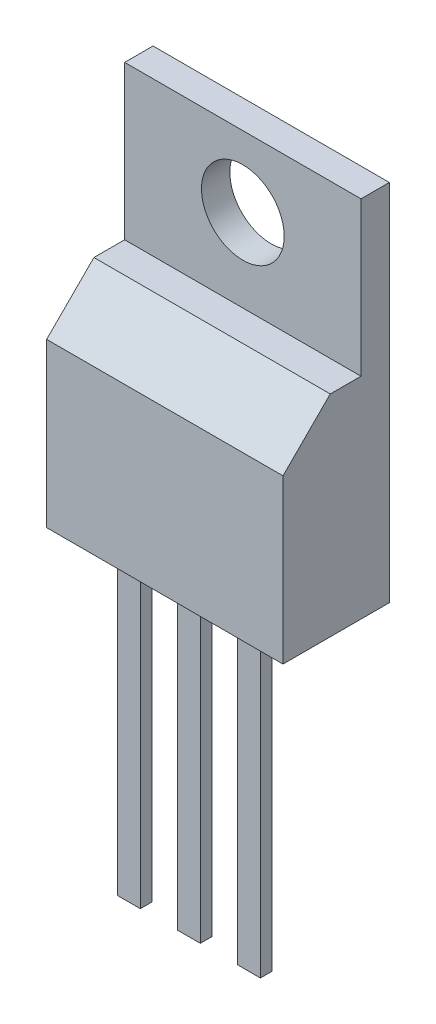
SolidWorks part; units mm, degrees
ref_plane "前视基准面" through (0, 0, 0) normal (0, 0, 1) x (1, 0, 0)
ref_plane "上视基准面" through (0, 0, 0) normal (0, 1, 0) x (1, 0, 0)
ref_plane "右视基准面" through (0, 0, 0) normal (1, 0, 0) x (0, 0, -1)
sketch "草图1" plane through (0, 0, 0) normal (0, 0, 1) x (1, 0, 0)
  line L0 (0, 13.5549) -> (0, -16.5771) construction
  line L1 (-5, 15.4) -> (5, 15.4)
  line L2 (-5, 15.4) -> (-5, 0)
  line L3 (-5, 0) -> (5, 0)
  line L4 (5, 15.4) -> (5, 0)
  line L5 (-12.7598, 0) -> (15.1062, 0) construction
  dimension "D1" = 15.4
  dimension "D2" = 10
extrude "凸台-拉伸1" add sketch "草图1" along normal blind 4.5
sketch "草图2" plane through (0, 0, 4.5) normal (0, 0, 1) x (1, 0, 0)
  line L0 (5, 0) -> (5, 15.4) construction
  line L1 (-5, 15.4) -> (5, 15.4)
  line L2 (-5, 15.4) -> (-5, 8.9)
  line L3 (-5, 8.9) -> (5, 8.9)
  line L4 (5, 15.4) -> (5, 8.9)
  dimension "D1" = 6.5
extrude "切除-拉伸1" cut sketch "草图2" against normal offset from surface (3.3 mm away) 1.2 up to face at (0, 7.7, 0)
chamfer "倒角1" distance 2 angle 45 1 edges at (0, 8.9, 4.5)
sketch "草图3" plane through (0, 0, 1.2) normal (0, 0, 1) x (1, 0, 0)
  line L0 (0, -0.804) -> (0, 16.0019) construction
  line L1 (-5, 15.4) -> (5, 15.4) construction
  circle A0 centre (0, 12.4) radius 1.75
  dimension "D2" = 3.5
  dimension "D1" = 3
extrude "切除-拉伸2" cut sketch "草图3" against normal through all
sketch "草图4" plane through (0, 0, 0) normal (0, -1, 0) x (1, 0, 0)
  line L0 (0, -1.662) -> (0, 5.2997) construction
  line L1 (-5.719, 3.23) -> (6.0741, 3.23) construction
  line L2 (-5, 4.5) -> (5, 4.5) construction
  line L3 (2.0572, 3.48) -> (3.0228, 3.48)
  line L4 (-0.4828, 3.48) -> (0.4828, 3.48)
  line L5 (-0.4828, 3.48) -> (-0.4828, 2.98)
  line L6 (-0.4828, 2.98) -> (0.4828, 2.98)
  line L7 (0.4828, 3.48) -> (0.4828, 2.98)
  line L8 (2.0572, 3.48) -> (2.0572, 2.98)
  line L9 (2.0572, 2.98) -> (3.0228, 2.98)
  line L10 (3.0228, 3.48) -> (3.0228, 2.98)
  line L11 (-3.0228, 3.48) -> (-2.0572, 3.48)
  line L12 (-3.0228, 3.48) -> (-3.0228, 2.98)
  line L13 (-3.0228, 2.98) -> (-2.0572, 2.98)
  line L14 (-2.0572, 3.48) -> (-2.0572, 2.98)
  dimension "D1" = 1.27
  dimension "D2" = 0.9656
  dimension "D3" = 0.5
  dimension "D4" = 2
  dimension "D5" = 2
extrude "凸台-拉伸2" add sketch "草图4" along normal blind 13
